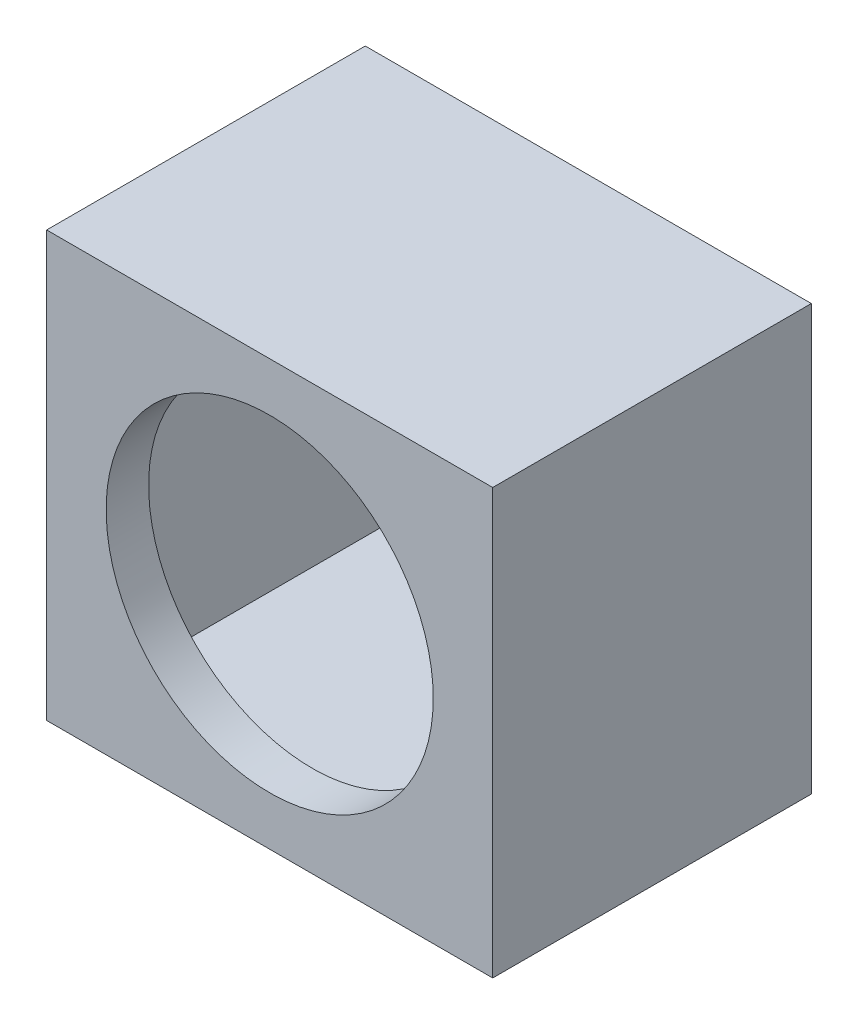
SolidWorks part; units mm, degrees
ref_plane "Front Plane" through (0, 0, 0) normal (0, 0, 1) x (1, 0, 0)
ref_plane "Top Plane" through (0, 0, 0) normal (0, 1, 0) x (1, 0, 0)
ref_plane "Right Plane" through (0, 0, 0) normal (1, 0, 0) x (0, 0, -1)
sketch "Sketch1" plane through (0, 0, 0) normal (0, 0, 1) x (1, 0, 0)
  line L1 (-5.25, -5) -> (5.25, -5)
  line L2 (-5.25, -5) -> (-5.25, 5)
  line L3 (-5.25, 5) -> (5.25, 5)
  line L4 (5.25, -5) -> (5.25, 5)
  line L5 (-5.25, -5) -> (5.25, 5) construction
  line L6 (-5.25, 5) -> (5.25, -5) construction
  point P0 (0, 0)
  dimension "D1" = 10
  dimension "D2" = 10.5
extrude "Boss-Extrude1" add sketch "Sketch1" along normal blind 7.5
shell "Shell1" thickness 1
sketch "Sketch2" plane through (0, 0, 7.5) normal (0, 0, 1) x (1, 0, 0)
  circle A0 centre (0, 0) radius 3.85
  dimension "D1" = 7.7
extrude "Cut-Extrude1" cut sketch "Sketch2" against normal up to next contours A0
sketch "Sketch3" plane through (0, 0, 0) normal (0, 0, 1) x (1, 0, 0)
  line L0 (4.25, 4) -> (-4.25, 4) construction
  line L1 (-4.25, -4) -> (4.25, -4)
  line L2 (-4.25, -4) -> (-4.25, 4)
  line L3 (-4.25, 4) -> (4.25, 4)
  line L4 (4.25, -4) -> (4.25, 4)
  line L5 (-4.25, -4) -> (4.25, 4) construction
  line L6 (-4.25, 4) -> (4.25, -4) construction
  line L7 (4.25, -4) -> (4.25, 4) construction
  point P1 (0, 0)
extrude "Cut-Extrude2" cut sketch "Sketch3" along normal blind 1
